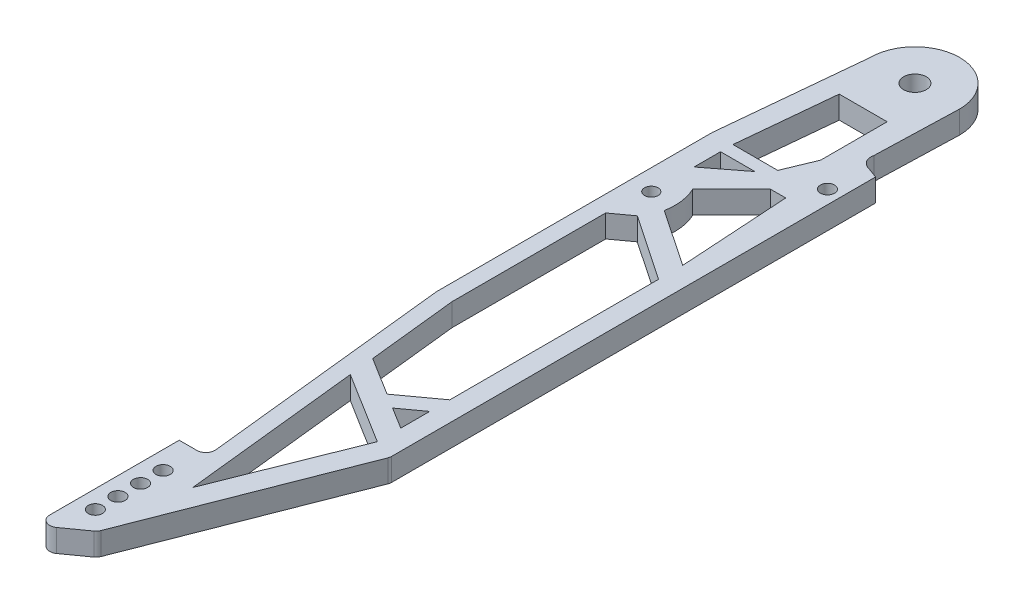
SolidWorks part; units mm, degrees
material "6061-T6 (SS)"
ref_plane "X-Y Datum" through (0, 0, 0) normal (0, 0, 1) x (1, 0, 0)
ref_plane "X-Z Datum" through (0, 0, 0) normal (0, 1, 0) x (1, 0, 0)
ref_plane "Y-Z Datum" through (0, 0, 0) normal (1, 0, 0) x (0, 0, -1)
other "Graphic1" [suppressed]
other "Graphic (Closed) -1" [suppressed]
sketch "Sketch2" plane through (0, 0, 0) normal (0, 1, 0) x (1, 0, 0)
  line L5 (-12.5603, 0) -> (-12.5603, -63.5) construction
  line L8 (0, 0) -> (0, -24.13) construction
  line L11 (0, -24.13) -> (18.0975, -24.13) construction
  line L14 (13.8466, -27.1172) -> (17.2959, -28.3595)
  line L15 (-16.51, -231.775) -> (-16.51, -190.417)
  line L16 (-16.51, -190.417) -> (-8.7218, -190.417)
  line L17 (-8.7218, -190.417) -> (-16.51, -118.11)
  line L18 (-16.51, -118.11) -> (-16.51, -40.5272)
  line L19 (-16.51, -40.5272) -> (-12.5603, 0)
  line L20 (11.8343, -23.3926) -> (12.5603, 0)
  line L21 (-16.51, -231.775) -> (-5.7887, -224.1061)
  line L22 (-5.7887, -224.1061) -> (17.2959, -164.9508)
  line L23 (17.2959, -164.9508) -> (17.2959, -28.3595)
  line L31 (-3.0884, -200.025) -> (-8.4371, -150.3674)
  line L32 (-8.4371, -150.3674) -> (11.7079, -162.9144)
  line L33 (11.7079, -162.9144) -> (-3.0884, -200.025)
  line L34 (5.6698, -152.5704) -> (11.7079, -156.3311)
  line L35 (11.7079, -156.3311) -> (11.7079, -148.1732)
  line L36 (11.7079, -148.1732) -> (5.6698, -152.5704)
  line L37 (-9.1972, -143.3108) -> (1.4836, -149.9631)
  line L38 (1.4836, -149.9631) -> (11.7079, -142.5174)
  line L39 (11.7079, -142.5174) -> (11.7079, -83.8261)
  line L40 (11.7079, -83.8261) -> (-6.7526, -71.3454)
  line L41 (-6.7526, -71.3454) -> (-11.8945, -75.0899)
  line L42 (-11.8945, -75.0899) -> (-11.8945, -118.2685)
  line L43 (-11.8945, -118.2685) -> (-9.1972, -143.3108)
  line L44 (-5.4504, -57.0473) -> (5.4772, -46.1198)
  line L45 (5.4772, -46.1198) -> (9.7706, -46.1198)
  line L46 (9.7706, -46.1198) -> (11.7079, -77.0374)
  line L47 (11.7079, -77.0374) -> (-4.2406, -66.255)
  line L48 (-5.4811, -40.5272) -> (-10.6553, -40.5272)
  line L49 (-10.6553, -40.5272) -> (-8.0015, -13.2972)
  line L50 (-8.0015, -13.2972) -> (5.4772, -13.2972)
  line L51 (5.4772, -13.2972) -> (5.4772, -31.9741)
  line L52 (5.4772, -31.9741) -> (1.9411, -40.5272)
  line L53 (1.9411, -40.5272) -> (-5.4811, -40.5272)
  line L54 (-10.6553, -44.0228) -> (-10.6553, -51.4721)
  line L55 (-10.6553, -51.4721) -> (-0.9913, -44.0228)
  line L56 (-0.9913, -44.0228) -> (-10.6553, -44.0228)
  circle A0 centre (0, 0) radius 3.175
  circle A2 centre (-11.43, -219.075) radius 2
  circle A3 centre (-11.43, -212.725) radius 2
  circle A4 centre (-11.43, -206.375) radius 2
  circle A5 centre (-11.43, -200.025) radius 2
  circle A7 centre (0, 0) radius 12.5603 construction
  circle A8 centre (-10.6553, -63.5) radius 1.905
  circle A9 centre (14.9225, -24.13) radius 3.175 construction
  arc A11 (13.8466, -27.1172) -> (11.8343, -23.3926) centre (14.9225, -24.13) cw
  circle A12 centre (13.4859, -38.1) radius 2
  arc A13 (-12.5603, 0) -> (12.5603, 0) centre (0, 0) cw
  arc A14 (-4.2406, -66.255) -> (-5.4504, -57.0473) centre (-18.9173, -63.5) ccw
  point P32 (18.0975, -24.13)
  point P60 (0, 0)
  point P62 (0, 0)
  point P63 (0, 0)
  point P64 (0, 0)
  dimension "D1" = 6.35
  dimension "D6" = 4
  dimension "D12" = 24.13
  dimension "D5" = 25.1206
  dimension "D14" = 3.81
  dimension "D19" = 4
  dimension "D20" = 6.35
  dimension "D24" = 83.852
  dimension "D50" = 14.933
  dimension "D51" = 8.262
  dimension "D3" = 40.7192
  dimension "D7" = 6.35
  dimension "D8" = 6.35
  dimension "D9" = 6.35
  dimension "D10" = 5.08
  dimension "D11" = 12.7
  dimension "D13" = 18.0975
  dimension "D15" = 77.5828
  dimension "D16" = 63.5
  dimension "D17" = 23.4039
  dimension "D18" = 63.5
  dimension "D21" = 136.5913
  dimension "D22" = 38.1
  dimension "D23" = 13.1818
  dimension "D25" = 41.358
  dimension "D26" = 3.81
  dimension "D27" = 3.6662
  dimension "D28" = 4.572
  dimension "D29" = 5.588
  dimension "D30" = 39.9516
  dimension "D31" = 5.1419
  dimension "D32" = 43.1786
  dimension "D33" = 185.566
  dimension "D34" = 54.424
  dimension "D35" = 5.624
  dimension "D36" = 5.588
  dimension "D37" = 247.98
  dimension "D38" = 12.6481
  dimension "D39" = 22.2836
  dimension "D40" = 51.936
  dimension "D41" = 4.572
  dimension "D42" = 16.51
  dimension "D43" = 200.025
  dimension "D45" = 4.6155
  dimension "D46" = 52.353
  dimension "D47" = 4.2935
  dimension "D48" = 135
  dimension "D49" = 15.4539
  dimension "D52" = 27.359
  dimension "D53" = 5.8271
  dimension "D54" = 18.6769
  dimension "D55" = 157.539
  dimension "D56" = 3.4956
  dimension "D57" = 52.374
  dimension "D58" = 12.0279
extrude "Boss-Extrude1" add sketch "Sketch2" along normal blind 6.35
fillet "Fillet2" radius 2.54 1 edges at (-8.7218, 3.175, 190.417)
fillet "Fillet3" radius 2.54 1 edges at (-5.7887, 3.175, 224.1061)
fillet "Fillet4" radius 2.54 1 edges at (-16.51, 3.175, 231.775)
fillet "Fillet5" radius 2.54 1 edges at (17.2959, 3.175, 164.9508)
